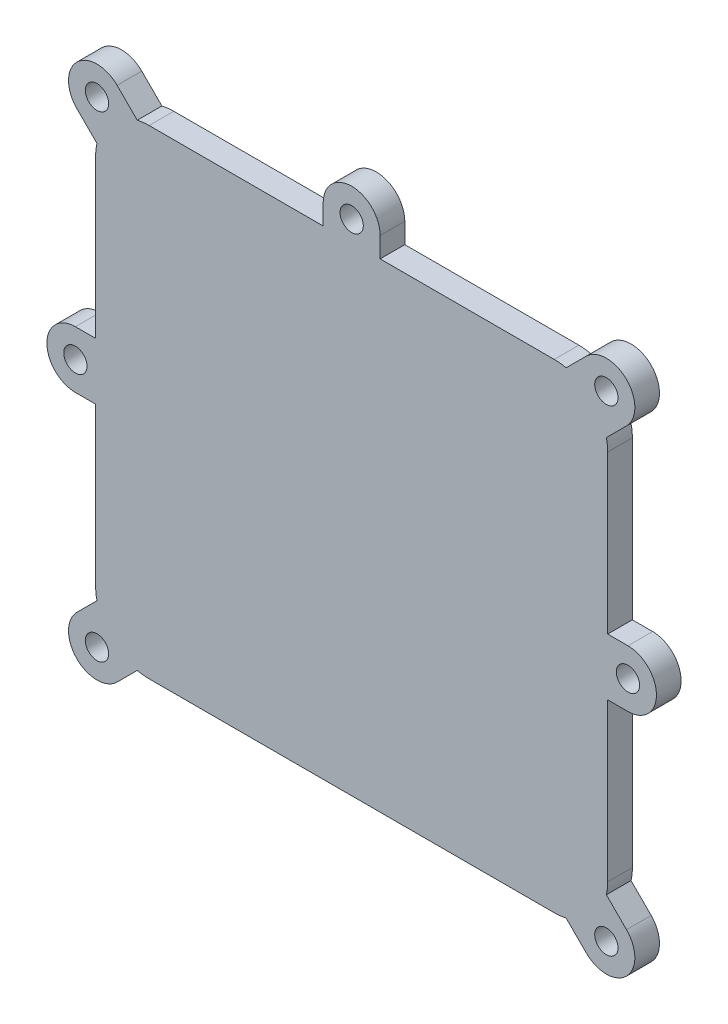
SolidWorks part; units mm, degrees
material "Acrylic (Medium-high impact)"
ref_plane "X-Y Datum" through (0, 0, 0) normal (0, 0, 1) x (1, 0, 0)
ref_plane "X-Z Datum" through (0, 0, 0) normal (0, 1, 0) x (1, 0, 0)
ref_plane "Y-Z Datum" through (0, 0, 0) normal (1, 0, 0) x (0, 0, -1)
sketch "Sketch1" plane through (0, 0, 0) normal (0, 0, 1) x (1, 0, 0)
  line L21 (237.4299, -1870.8345) -> (203.8139, -1870.8345)
  line L60 (282.0459, -1870.8345) -> (248.4299, -1870.8345)
  line L61 (248.4299, -1870.8345) -> (248.4299, -1866.9248)
  line L62 (237.4299, -1866.9248) -> (237.4299, -1870.8345)
  line L63 (237.4299, -1870.8345) -> (203.8139, -1870.8345)
  line L64 (201.5167, -1871.0931) -> (197.6312, -1867.2076)
  line L65 (189.853, -1874.9858) -> (193.7385, -1878.8712)
  line L66 (193.4799, -1881.1685) -> (193.4799, -1911.6095)
  line L67 (193.4799, -1911.6095) -> (189.5702, -1911.6095)
  line L68 (189.5702, -1922.6095) -> (193.4799, -1922.6095)
  line L69 (193.4799, -1922.6095) -> (193.4799, -1953.0505)
  line L70 (193.7385, -1955.3477) -> (189.853, -1959.2332)
  line L71 (197.6312, -1967.0114) -> (201.5167, -1963.1259)
  line L72 (193.4799, -1881.1685) -> (193.4799, -1911.6095)
  line L73 (193.4799, -1911.6095) -> (189.5702, -1911.6095)
  line L74 (189.5702, -1922.6095) -> (193.4799, -1922.6095)
  line L75 (193.4799, -1922.6095) -> (193.4799, -1953.0505)
  line L76 (193.7385, -1955.3477) -> (189.853, -1959.2332)
  line L77 (197.6312, -1967.0114) -> (201.5167, -1963.1259)
  line L78 (203.8139, -1963.3845) -> (282.0459, -1963.3845)
  line L79 (284.3432, -1963.1259) -> (288.2287, -1967.0114)
  line L80 (296.0068, -1959.2332) -> (292.1213, -1955.3477)
  line L81 (292.3799, -1953.0505) -> (292.3799, -1922.6095)
  line L82 (292.3799, -1922.6095) -> (296.2896, -1922.6095)
  line L83 (296.2896, -1911.6095) -> (292.3799, -1911.6095)
  line L84 (292.3799, -1911.6095) -> (292.3799, -1881.1685)
  line L85 (292.1213, -1878.8712) -> (296.0068, -1874.9858)
  line L86 (288.2287, -1867.2076) -> (284.3432, -1871.0931)
  line L87 (282.0459, -1870.8345) -> (248.4299, -1870.8345)
  line L88 (201.5167, -1871.0931) -> (197.6312, -1867.2076)
  line L89 (189.853, -1874.9858) -> (193.7385, -1878.8712)
  line L90 (203.8139, -1963.3845) -> (282.0459, -1963.3845)
  line L91 (284.3432, -1963.1259) -> (288.2287, -1967.0114)
  line L92 (296.0068, -1959.2332) -> (292.1213, -1955.3477)
  line L93 (292.3799, -1953.0505) -> (292.3799, -1922.6095)
  line L94 (292.3799, -1922.6095) -> (296.2896, -1922.6095)
  line L95 (296.2896, -1911.6095) -> (292.3799, -1911.6095)
  line L96 (292.3799, -1911.6095) -> (292.3799, -1881.1685)
  line L97 (292.1213, -1878.8712) -> (296.0068, -1874.9858)
  line L98 (288.2287, -1867.2076) -> (284.3432, -1871.0931)
  arc A44 (248.4299, -1866.9248) -> (237.4299, -1866.9248) centre (242.9299, -1866.9248) ccw
  arc A45 (203.8139, -1870.8345) -> (201.5167, -1871.0931) centre (203.8139, -1881.1685) ccw
  arc A46 (197.6312, -1867.2076) -> (189.853, -1874.9858) centre (193.7421, -1871.0967) ccw
  arc A47 (193.7385, -1878.8712) -> (193.4799, -1881.1685) centre (203.8139, -1881.1685) ccw
  arc A48 (189.5702, -1911.6095) -> (189.5702, -1922.6095) centre (189.5702, -1917.1095) ccw
  arc A49 (193.4799, -1953.0505) -> (193.7385, -1955.3477) centre (203.8139, -1953.0505) ccw
  arc A50 (189.853, -1959.2332) -> (197.6312, -1967.0114) centre (193.7421, -1963.1223) ccw
  arc A51 (201.5167, -1963.1259) -> (203.8139, -1963.3845) centre (203.8139, -1953.0505) ccw
  arc A52 (282.0459, -1963.3845) -> (284.3432, -1963.1259) centre (282.0459, -1953.0505) ccw
  arc A53 (288.2287, -1967.0114) -> (296.0068, -1959.2332) centre (292.1177, -1963.1223) ccw
  arc A54 (292.1213, -1955.3477) -> (292.3799, -1953.0505) centre (282.0459, -1953.0505) ccw
  arc A55 (296.2896, -1922.6095) -> (296.2896, -1911.6095) centre (296.2896, -1917.1095) ccw
  arc A56 (189.5702, -1911.6095) -> (189.5702, -1922.6095) centre (189.5702, -1917.1095) ccw
  arc A57 (193.4799, -1953.0505) -> (193.7385, -1955.3477) centre (203.8139, -1953.0505) ccw
  arc A58 (189.853, -1959.2332) -> (197.6312, -1967.0114) centre (193.7421, -1963.1223) ccw
  arc A59 (201.5167, -1963.1259) -> (203.8139, -1963.3845) centre (203.8139, -1953.0505) ccw
  arc A60 (282.0459, -1963.3845) -> (284.3432, -1963.1259) centre (282.0459, -1953.0505) ccw
  arc A61 (288.2287, -1967.0114) -> (296.0068, -1959.2332) centre (292.1177, -1963.1223) ccw
  arc A62 (292.1213, -1955.3477) -> (292.3799, -1953.0505) centre (282.0459, -1953.0505) ccw
  arc A63 (296.2896, -1922.6095) -> (296.2896, -1911.6095) centre (296.2896, -1917.1095) ccw
  arc A64 (292.3799, -1881.1685) -> (292.1213, -1878.8712) centre (282.0459, -1881.1685) ccw
  arc A65 (296.0068, -1874.9858) -> (288.2287, -1867.2076) centre (292.1177, -1871.0967) ccw
  arc A66 (284.3432, -1871.0931) -> (282.0459, -1870.8345) centre (282.0459, -1881.1685) ccw
  arc A67 (203.8139, -1870.8345) -> (201.5167, -1871.0931) centre (203.8139, -1881.1685) ccw
  arc A68 (197.6312, -1867.2076) -> (189.853, -1874.9858) centre (193.7421, -1871.0967) ccw
  arc A69 (193.7385, -1878.8712) -> (193.4799, -1881.1685) centre (203.8139, -1881.1685) ccw
  arc A70 (292.3799, -1881.1685) -> (292.1213, -1878.8712) centre (282.0459, -1881.1685) ccw
  arc A71 (296.0068, -1874.9858) -> (288.2287, -1867.2076) centre (292.1177, -1871.0967) ccw
  arc A72 (284.3432, -1871.0931) -> (282.0459, -1870.8345) centre (282.0459, -1881.1685) ccw
extrude "Boss-Extrude1" add sketch "Sketch1" along normal blind 4.7625 contours L86 A66 L60 L61 A44 L62 L21 A45 L64 A46 L65 A47 L66 L67 A48 L68 L69 A49 L70 A50 L71 A51 L78 A52 L79 A53 L80 A54 L81 L82 A55 L83 L84 A64 L85 A65
hole_wizard "M4 Clearance Hole1" positions "Sketch2" profile "Sketch3" hole size "M4" standard "ANSI Metric" end condition through all
sketch "Sketch2" plane through (0, 0, 4.7625) normal (0, 0, 1) x (1, 0, 0)
  point P0 (193.7421, -1963.1223)
  point P2 (189.5702, -1917.1095)
  point P4 (193.7421, -1871.0967)
  point P6 (242.9299, -1866.9248)
  point P8 (292.1177, -1871.0967)
  point P10 (296.2896, -1917.1095)
  point P12 (292.1177, -1963.1223)
sketch "Sketch3" plane through (193.7421, -1963.1223, 4.7625) normal (1, 0, 0) x (0, -1, 0)
  line L0 (0, 0) -> (0, 4.7625)
  line L1 (0, 4.7625) -> (2.25, 4.7625)
  line L2 (2.25, 4.7625) -> (2.25, 0)
  line L5 (2.25, 0) -> (0, 0)
  line L11 (0, -6.35) -> (0, 107.95) construction
  dimension "Thru Hole Dia." = 4.5
  dimension "Thru Hole Depth" = 4.7625
